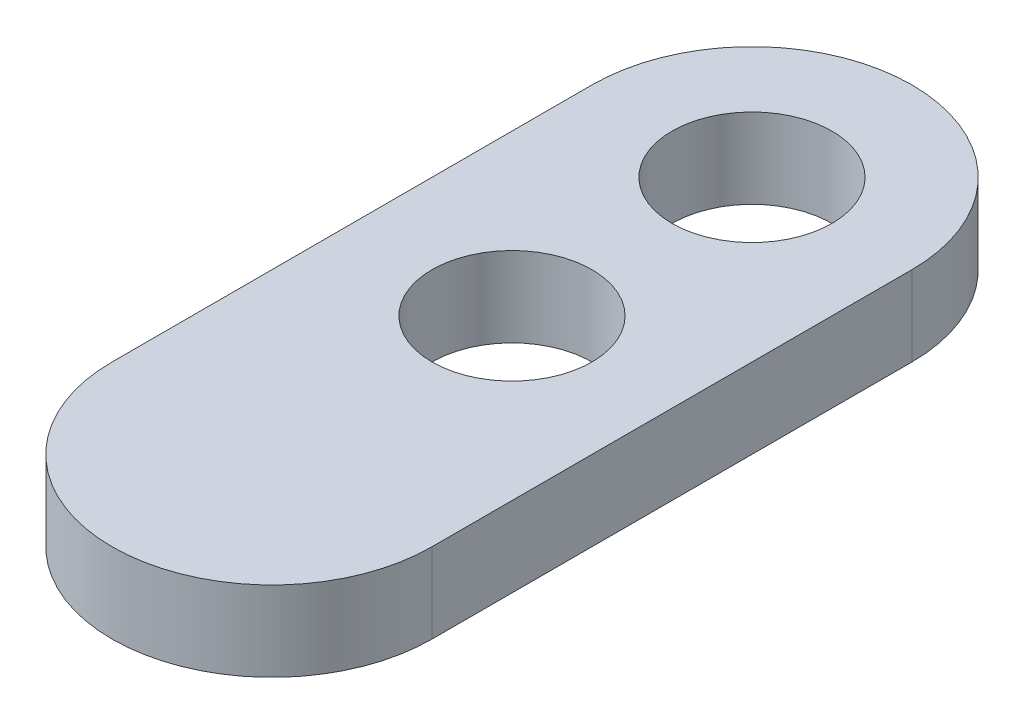
SolidWorks part; units mm, degrees
ref_plane "Front" through (0, 0, 0) normal (0, 0, 1) x (1, 0, 0)
ref_plane "Top" through (0, 0, 0) normal (0, 1, 0) x (1, 0, 0)
ref_plane "Right" through (0, 0, 0) normal (1, 0, 0) x (0, 0, -1)
sketch "Sketch1" plane through (0, 0, 0) normal (0, 1, 0) x (1, 0, 0)
  line L1 (-5, -7.5) -> (5, -7.5)
  line L2 (-5, -7.5) -> (-5, 7.5)
  line L3 (-5, 7.5) -> (5, 7.5)
  line L4 (5, -7.5) -> (5, 7.5)
  line L5 (-5, -7.5) -> (5, 7.5) construction
  line L6 (-5, 7.5) -> (5, -7.5) construction
  arc A0 (-5, 7.5) -> (5, 7.5) centre (0, 7.5) cw
  arc A1 (-5, -7.5) -> (5, -7.5) centre (0, -7.5) ccw
  point P0 (0, 0)
  dimension "D1" = 10
  dimension "D2" = 15
extrude "Boss-Extrude1" add sketch "Sketch1" along normal blind 2.5 contours A0 L3 | L1 L4 L3 L2 | L1 A1
sketch "Sketch2" plane through (0, 2.5, 0) normal (0, 1, 0) x (1, 0, 0)
  circle A0 centre (0, 7.5) radius 2.5
  arc A3 (5, 7.5) -> (-5, 7.5) centre (0, 7.5) ccw construction
  circle A4 centre (0, 0) radius 2.5
  dimension "D1" = 5
  dimension "D2" = 7.5
extrude "Cut-Extrude1" cut sketch "Sketch2" against normal up to next
